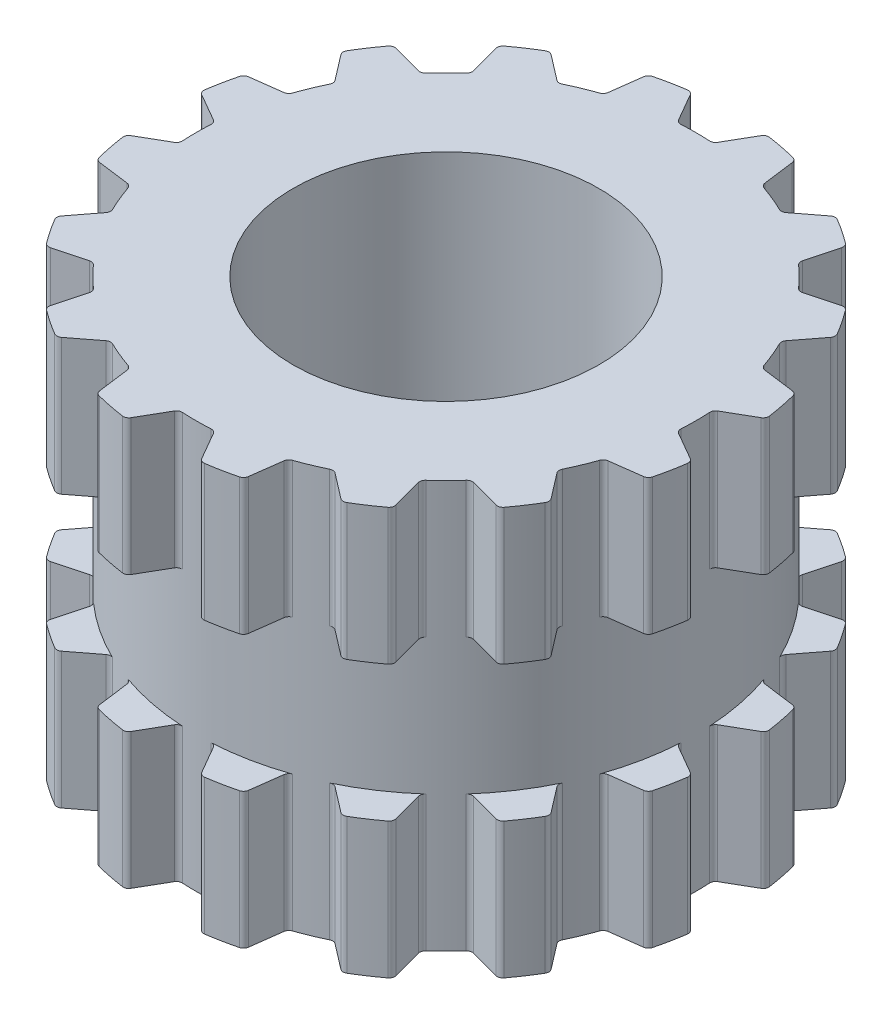
SolidWorks part; units mm, degrees
material "Brass"
ref_plane "Front Plane" through (0, 0, 0) normal (0, 0, 1) x (1, 0, 0)
ref_plane "Top Plane" through (0, 0, 0) normal (0, 1, 0) x (1, 0, 0)
ref_plane "Right Plane" through (0, 0, 0) normal (1, 0, 0) x (0, 0, -1)
ref_axis "CentralAxis" through (0, 5.5, 0) along (0, -1, 0)
sketch "BodyS" plane through (0, 0, 0) normal (0, 0, 1) x (1, 0, 0)
  line L0 (0, 1.5) -> (2, 1.5)
  line L1 (2, 1.5) -> (2, -1.5)
  line L6 (2, -1.5) -> (0, -1.5)
  line L7 (0, -1.5) -> (0, 1.5) construction
  dimension "Height" = 3
  dimension "ThreadInsertDiameter" = 4
revolve "Body" add sketch "BodyS" angle 360 about L7
hole_wizard "M3x0.5 Tapped Hole1" positions "Sketch2" profile "Sketch3" tap size "M3x0.5" standard "ANSI Metric" end condition through all
sketch "Sketch2" plane through (0, 1.5, 0) normal (0, 1, 0) x (1, 0, 0)
  point P0 (0, 0)
sketch "Sketch3" plane through (0, 1.5, 0) normal (1, 0, 0) x (0, 0, 1)
  line L0 (0, 0) -> (0, 3)
  line L1 (0, 3) -> (1.25, 3)
  line L2 (1.25, 3) -> (1.25, 0)
  line L5 (1.25, 0) -> (0, 0)
  line L11 (0, -6.35) -> (0, 107.95) construction
  dimension "Thru Tap Drill Dia." = 2.5
  dimension "Thru Tap Drill Depth" = 3
cosmetic thread "Hole Thread1" parameters "D2"=3
sketch "MidBodyCutS" plane through (0, 0, 0) normal (0, 0, 1) x (1, 0, 0)
  line L1 (2, 0.5) -> (1.75, 0.5)
  line L2 (2, 0.5) -> (2, -0.5)
  line L3 (2, -0.5) -> (1.75, -0.5)
  line L4 (1.75, 0.5) -> (1.75, -0.5)
  line L5 (2, 0.5) -> (1.75, -0.5) construction
  line L6 (2, -0.5) -> (1.75, 0.5) construction
  line L7 (2, -1.5) -> (2, 1.5) construction
  line L8 (0, 0) -> (1.875, 0) construction
  line L9 (2, 1.5) -> (-2, 1.5) construction
  point P0 (1.875, 0)
  dimension "Width" = 0.25
  dimension "RefHeight" = 1
  dimension "Height" = 1
revolve "MidBodyCut" cut sketch "MidBodyCutS" angle 360 about axis through (0, 5.5, 0) along (0, -1, 0)
sketch "GrooveCutS" plane through (0, 0, 0) normal (0, 1, 0) x (1, 0, 0)
  line L4 (0, 0) -> (0, 1.75) construction
  line L5 (0.1369, 1.7671) -> (0.248, 1.9595)
  line L6 (0, 1.75) -> (0, 2) construction
  line L7 (-0.1369, 1.7671) -> (-0.248, 1.9595)
  circle A0 centre (0, 0) radius 1.75 construction
  circle A1 centre (0, 0) radius 2 construction
  arc A2 (0.0999, 1.7471) -> (-0.0999, 1.7471) centre (0, 0) ccw
  arc A3 (0.2884, 1.9791) -> (-0.2884, 1.9791) centre (0, 0) ccw
  arc A4 (0.248, 1.9595) -> (0.2884, 1.9791) centre (0.2826, 1.9395) cw
  arc A5 (0.1369, 1.7671) -> (0.0999, 1.7471) centre (0.1022, 1.7871) cw
  arc A6 (-0.248, 1.9595) -> (-0.2884, 1.9791) centre (-0.2826, 1.9395) ccw
  arc A7 (-0.1369, 1.7671) -> (-0.0999, 1.7471) centre (-0.1022, 1.7871) ccw
  point P14 (0.1245, 1.7456)
  dimension "RefInnerDiameter" = 3.5
  dimension "InnerRadius" = 0.04
  dimension "OuterRadius" = 0.04
  dimension "Depth" = 0.25
  dimension "Angle" = 60
  dimension "RefOuterWidth" = 0.5768
  dimension "InnerArcWidth" = 0.2
extrude "GrooveCut" cut sketch "GrooveCutS" against normal through all both and the other way through all
pattern_circular "GCCP" count 16 over 360 about axis through (0, 0, 0) along (0, 1, 0) of "GrooveCut"
scale "Scale1" scale about origin uniform scaling no x scale factor 1.4 y scale factor 1.333 z scale factor 1.4
sketch "Sketch4" plane through (0, 1.9995, 0) normal (0, 1, 0) x (1, 0, 0)
  circle A0 centre (0, 0) radius 1.5
  circle A1 centre (0, 0) radius 1.75
extrude "Boss-Extrude1" add sketch "Sketch4" against normal up to surface (3.999 mm away) up to face at (0, -1.9995, 1.75)
